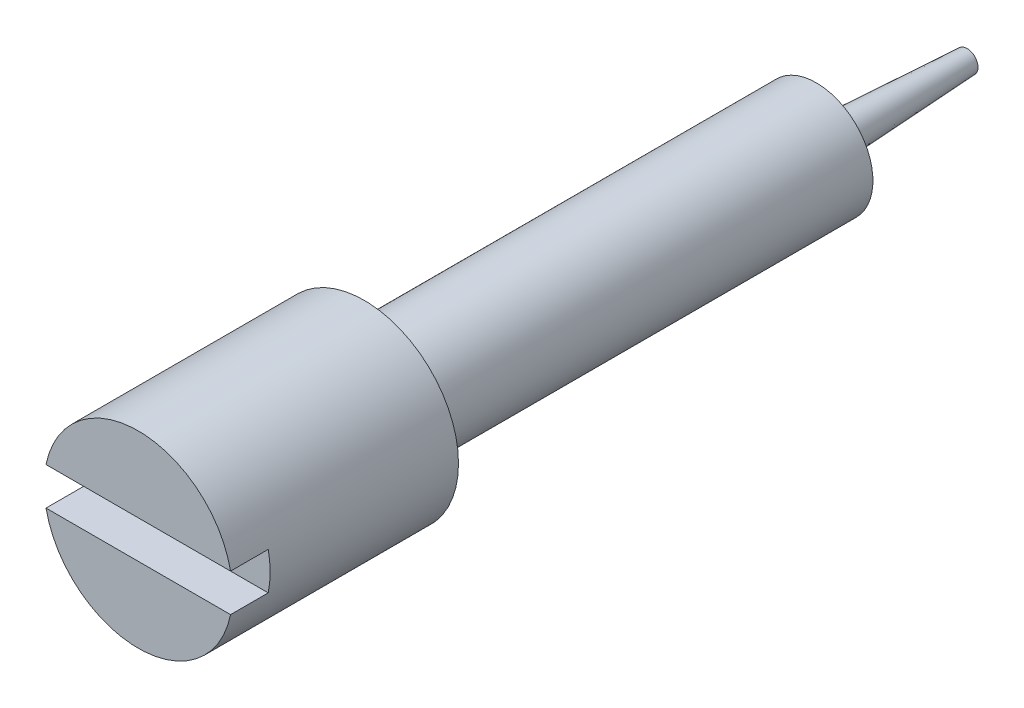
SolidWorks part; units mm, degrees
material "Stainless Steel (ferritic)"
ref_plane "Front" through (0, 0, 0) normal (0, 0, 1) x (1, 0, 0)
ref_plane "Top" through (0, 0, 0) normal (0, 1, 0) x (1, 0, 0)
ref_plane "Right" through (0, 0, 0) normal (1, 0, 0) x (0, 0, -1)
sketch "Sketch1" plane through (0, 0, 0) normal (0, 0, 1) x (1, 0, 0)
  circle A0 centre (0, 0) radius 2.5
extrude "Boss-Extrude1" add sketch "Sketch1" along normal blind 6
sketch "Sketch2" plane through (0, 0, 6) normal (0, 0, 1) x (1, 0, 0)
  line L1 (-2.6843, 0.5) -> (2.6843, 0.5)
  line L2 (-2.6843, 0.5) -> (-2.6843, -0.5)
  line L3 (-2.6843, -0.5) -> (2.6843, -0.5)
  line L4 (2.6843, 0.5) -> (2.6843, -0.5)
  line L5 (-2.6843, 0.5) -> (2.6843, -0.5) construction
  line L6 (-2.6843, -0.5) -> (2.6843, 0.5) construction
  point P0 (0, 0)
extrude "Cut-Extrude1" cut sketch "Sketch2" against normal blind 1
sketch "Sketch3" plane through (0, 0, 0) normal (0, 0, -1) x (-1, 0, 0)
  circle A0 centre (0, 0) radius 1.5
extrude "Boss-Extrude2" add sketch "Sketch3" along normal blind 12
cosmetic thread "Cosmetic Thread1" parameters "D2"=2.439
sketch "Sketch4" plane through (0, 0, -12) normal (0, 0, -1) x (-1, 0, 0)
  circle A0 centre (0, 0) radius 0.5
extrude "Boss-Extrude3" add sketch "Sketch4" along normal blind 4 draft 3
